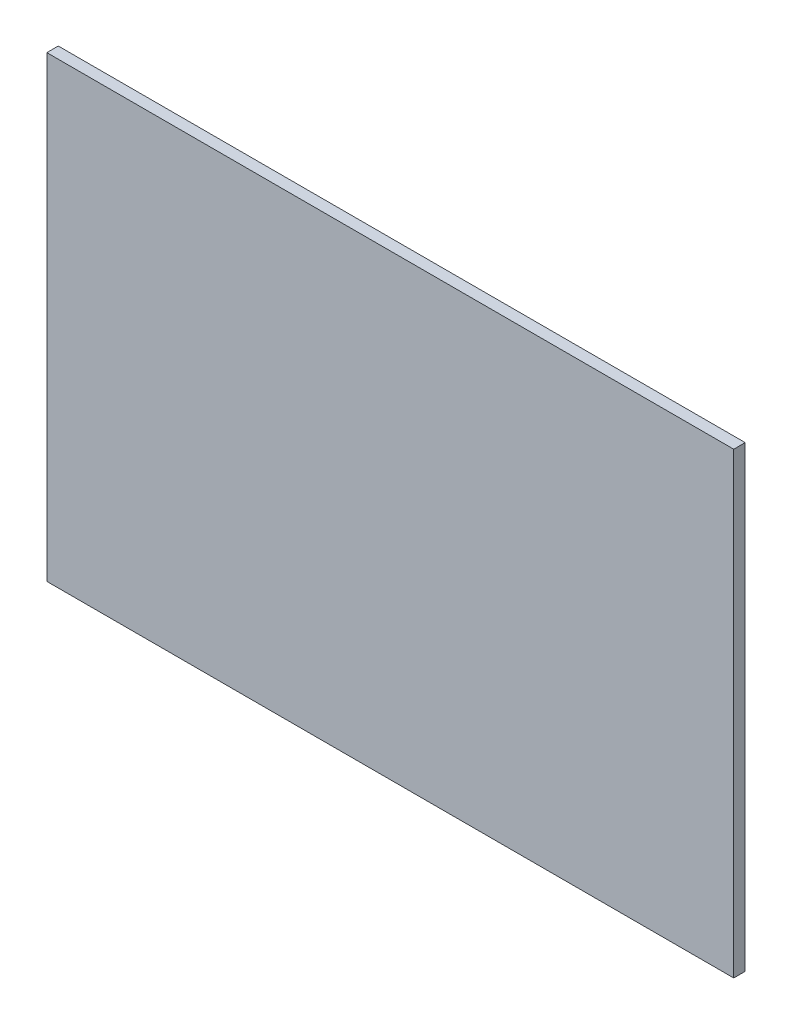
SolidWorks part; units mm, degrees
ref_plane "前视基准面" through (0, 0, 0) normal (0, 0, 1) x (1, 0, 0)
ref_plane "上视基准面" through (0, 0, 0) normal (0, 1, 0) x (1, 0, 0)
ref_plane "右视基准面" through (0, 0, 0) normal (1, 0, 0) x (0, 0, -1)
sketch "草图1" plane through (0, 0, 0) normal (0, 0, 1) x (1, 0, 0)
  line L1 (-90, 60) -> (90, 60)
  line L2 (-90, 60) -> (-90, -60)
  line L3 (-90, -60) -> (90, -60)
  line L4 (90, 60) -> (90, -60)
  line L5 (-90, 60) -> (90, -60) construction
  line L6 (-90, -60) -> (90, 60) construction
  point P0 (0, 0)
  dimension "D1" = 120
  dimension "D2" = 180
extrude "凸台-拉伸1" add sketch "草图1" along normal blind 3
